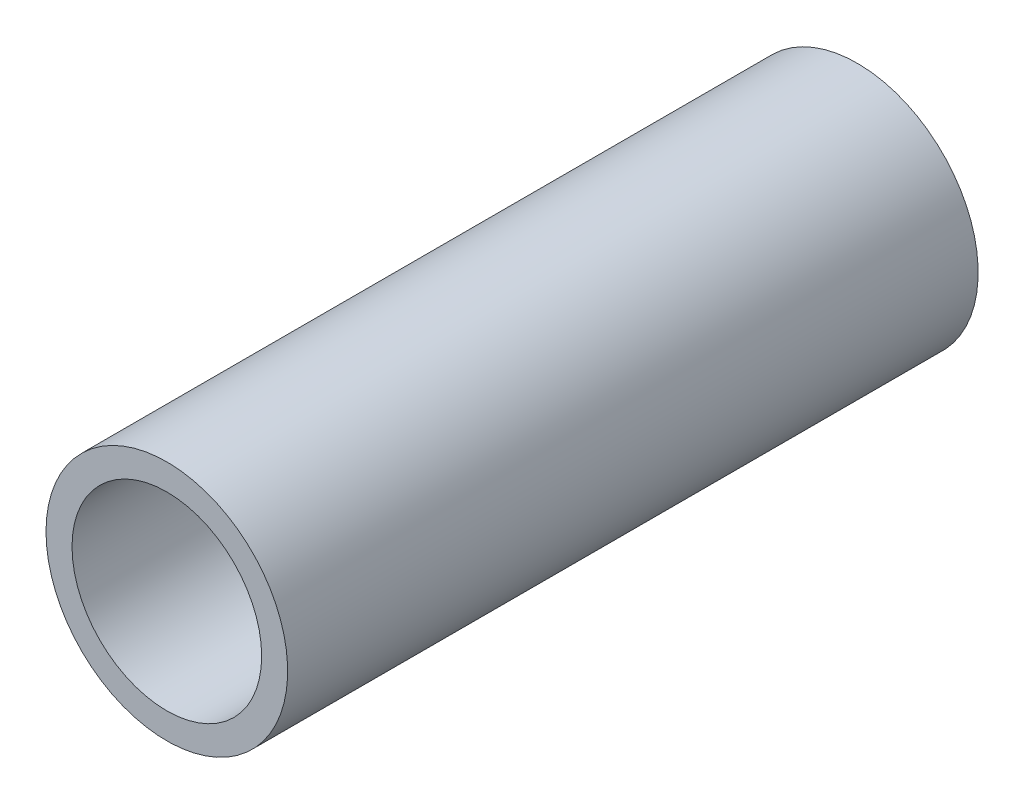
SolidWorks part; units mm, degrees
ref_plane "Front Plane" through (0, 0, 0) normal (0, 0, 1) x (1, 0, 0)
ref_plane "Top Plane" through (0, 0, 0) normal (0, 1, 0) x (1, 0, 0)
ref_plane "Right Plane" through (0, 0, 0) normal (1, 0, 0) x (0, 0, -1)
sketch "Sketch1" plane through (0, 0, 0) normal (0, 0, 1) x (1, 0, 0)
  circle A0 centre (0, 0) radius 10.4648
  circle A1 centre (0, 0) radius 13.335
  dimension "D1" = 2.8702
  dimension "D2" = 26.67
extrude "Boss-Extrude1" add sketch "Sketch1" along normal blind 76.2
